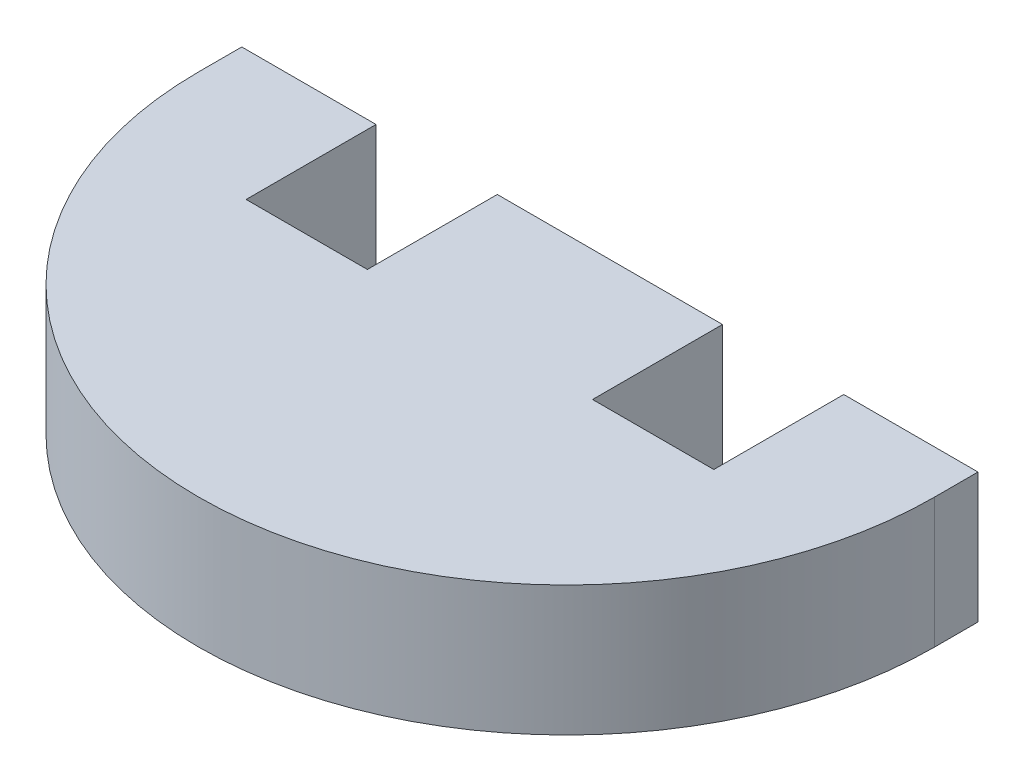
SolidWorks part; units mm, degrees
ref_plane "Front Plane" through (0, 0, 0) normal (0, 0, 1) x (1, 0, 0)
ref_plane "Top Plane" through (0, 0, 0) normal (0, 1, 0) x (1, 0, 0)
ref_plane "Right Plane" through (0, 0, 0) normal (1, 0, 0) x (0, 0, -1)
sketch "Sketch1" plane through (0, 0, 0) normal (0, 1, 0) x (1, 0, 0)
  line L1 (-8.5, 0) -> (-8.5, 1)
  line L2 (-8.5, 1) -> (8.5, 1)
  line L3 (8.5, 1) -> (8.5, 0)
  arc A0 (-8.5, 0) -> (8.5, 0) centre (0, 0) ccw
  dimension "D1" = 17
  dimension "D2" = 1
extrude "Boss-Extrude1" add sketch "Sketch1" along normal blind 3
sketch "Sketch2" plane through (0, 3, 0) normal (0, 1, 0) x (1, 0, 0)
  line L0 (-8.5, 1) -> (-5.4, 1) construction
  line L2 (0, 0) -> (0, -1.5) construction
  line L3 (-5.4, 1) -> (-2.6, 1)
  line L4 (-5.4, 1) -> (-5.4, -2)
  line L5 (-5.4, -2) -> (-2.6, -2)
  line L6 (-2.6, 1) -> (-2.6, -2)
  line L7 (-5.4, 1) -> (-2.6, -2) construction
  line L8 (-5.4, -2) -> (-2.6, 1) construction
  line L9 (5.4, -2) -> (2.6, 1) construction
  line L10 (5.4, 1) -> (2.6, -2) construction
  line L11 (8.5, 1) -> (5.4, 1) construction
  line L16 (2.6, 1) -> (2.6, -2)
  line L17 (5.4, -2) -> (2.6, -2)
  line L18 (5.4, 1) -> (5.4, -2)
  line L19 (5.4, 1) -> (2.6, 1)
  point P8 (-4, -0.5)
  point P16 (4, -0.5)
  dimension "D1" = 3
  dimension "D2" = 3.1
  dimension "D3" = 2.8
extrude "Cut-Extrude1" cut sketch "Sketch2" against normal through all
